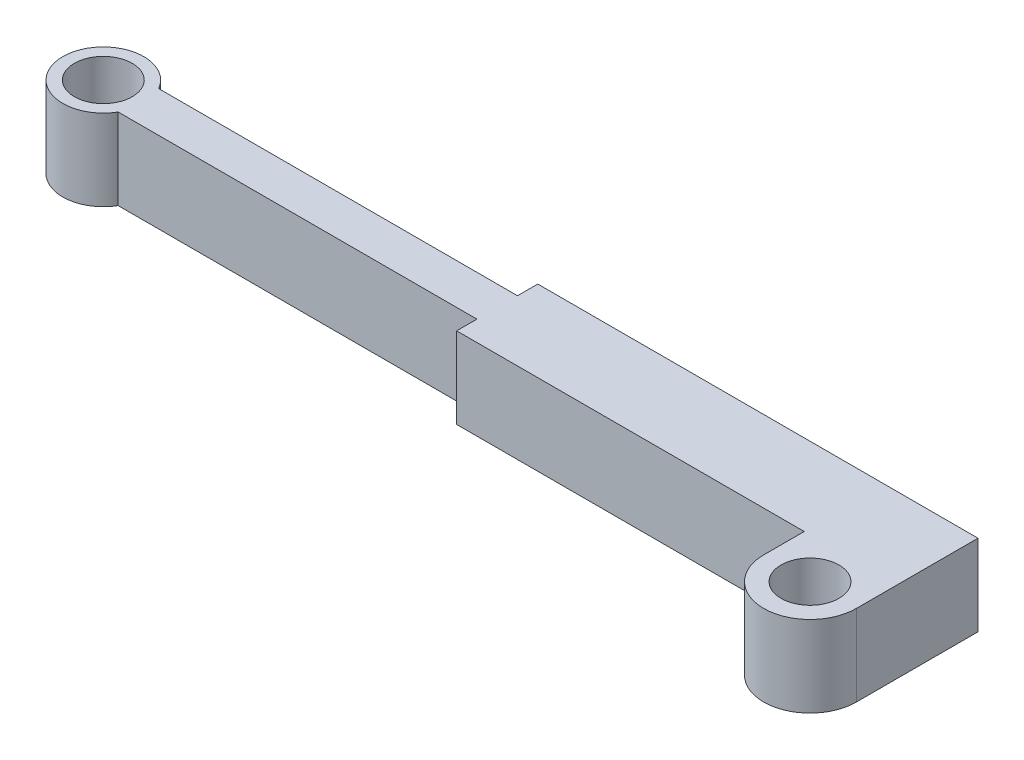
SolidWorks part; units mm, degrees
ref_plane "Front" through (0, 0, 0) normal (0, 0, 1) x (1, 0, 0)
ref_plane "Top" through (0, 0, 0) normal (0, 1, 0) x (1, 0, 0)
ref_plane "Right" through (0, 0, 0) normal (1, 0, 0) x (0, 0, -1)
sketch "Sketch1" plane through (0, 0, 0) normal (0, 1, 0) x (1, 0, 0)
  line L0 (38, 3.5) -> (68, 3.5)
  line L4 (76, -7) -> (76, 0)
  line L6 (68, 0) -> (68, 3.5)
  line L7 (68, -3.5) -> (68, -7)
  line L8 (68, 3.5) -> (76, 3.5)
  line L9 (76, 3.5) -> (76, 0)
  line L10 (38, -3.5) -> (68, -3.5)
  line L16 (38, -1.75) -> (8, -1.75)
  line L17 (8, 1.75) -> (38, 1.75)
  line L18 (38, 1.75) -> (38, 3.5)
  line L19 (38, -1.75) -> (38, -3.5)
  line L20 (8, 1.75) -> (7.0311, 1.75)
  line L21 (8, -1.75) -> (7.0311, -1.75)
  circle A2 centre (4, 0) radius 2.5
  circle A3 centre (72, -7) radius 2.5
  arc A4 (68, -7) -> (76, -7) centre (72, -7) ccw
  arc A5 (4, 3.5) -> (4, -3.5) centre (4, 0) ccw
  arc A6 (4, 3.5) -> (4, -3.5) centre (4, 0) cw
  dimension "D2" = 8
  dimension "D5" = 3.5
  dimension "D6" = 3.5
extrude "Boss-Extrude1" add sketch "Sketch1" along normal blind 7
sketch "Sketch2" plane through (76, 0, 0) normal (1, 0, 0) x (0, 0, -1)
  line L0 (-7, 7) -> (3.5, 7) construction
  line L1 (-7, 0) -> (3.5, 0) construction
  line L2 (-1.75, 7) -> (3.5, 7)
  line L3 (3.5, 7) -> (3.5, 0)
  line L4 (3.5, 0) -> (-1.75, 0)
  arc A0 (-1.75, 7) -> (-1.75, 0) centre (-1.75, 3.5) cw
